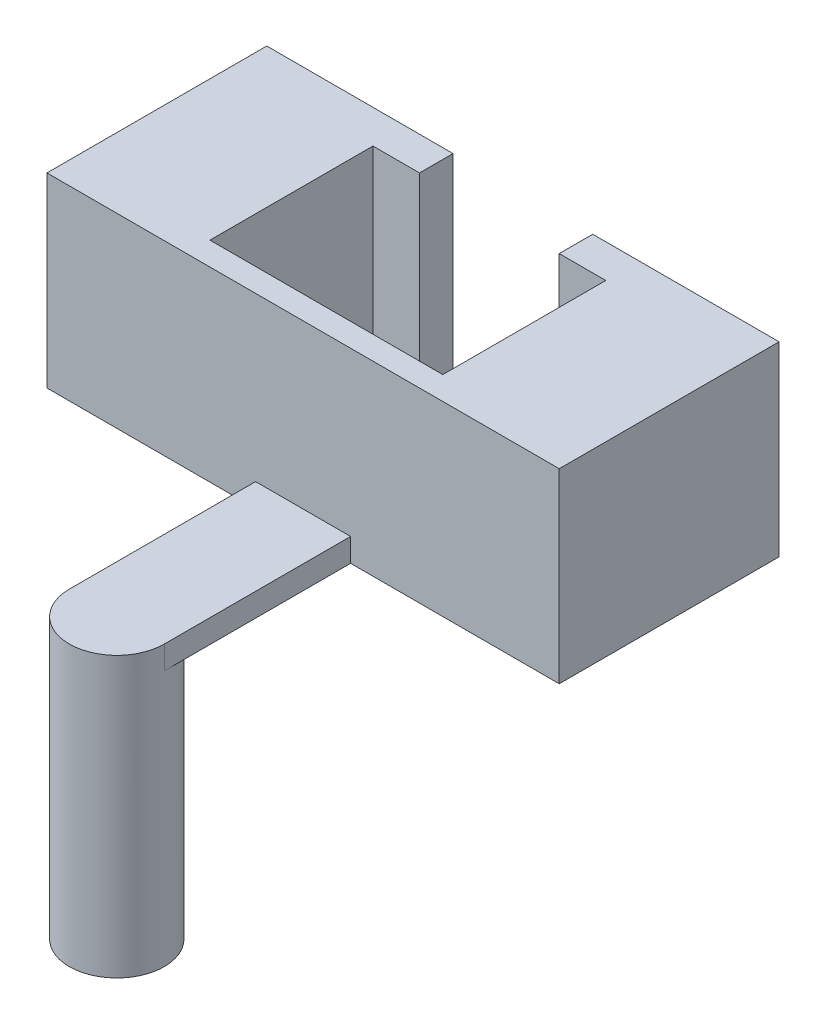
SolidWorks part; units mm, degrees
ref_plane "Front Plane" through (0, 0, 0) normal (0, 0, 1) x (1, 0, 0)
ref_plane "Top Plane" through (0, 0, 0) normal (0, 1, 0) x (1, 0, 0)
ref_plane "Right Plane" through (0, 0, 0) normal (1, 0, 0) x (0, 0, -1)
sketch "Sketch1" plane through (0, 0, 0) normal (0, 1, 0) x (1, 0, 0)
  circle A0 centre (-1.7341, 7.7072) radius 12.954
  dimension "D1" = 25.908
extrude "Boss-Extrude1" add sketch "Sketch1" along normal blind 76.2 contours A0
sketch "Sketch3" plane through (0, 76.2, 0) normal (0, 1, 0) x (1, 0, 0)
  line L1 (-14.6881, 7.7072) -> (11.2199, 7.7072)
  line L2 (-14.6881, 7.7072) -> (-14.6881, 58.5072)
  line L3 (-14.6881, 58.5072) -> (11.2199, 58.5072)
  line L4 (11.2199, 7.7072) -> (11.2199, 58.5072)
  circle A0 centre (-1.7341, 7.7072) radius 12.954 construction
  dimension "D1" = 50.8
  dimension "D2" = 25.908
extrude "Boss-Extrude3" add sketch "Sketch3" against normal blind 6.35
sketch "Sketch7" plane through (0, 0, -58.5072) normal (0, 0, -1) x (-1, 0, 0)
  line L0 (-11.2199, 69.85) -> (14.6881, 69.85) construction
  line L1 (-30.0159, 120.65) -> (33.4841, 120.65)
  line L2 (-30.0159, 120.65) -> (-30.0159, 69.85)
  line L3 (-30.0159, 69.85) -> (33.4841, 69.85)
  line L4 (33.4841, 120.65) -> (33.4841, 69.85)
  point P6 (1.7341, 69.85)
  point P7 (1.7341, 69.85)
  dimension "D1" = 50.8
  dimension "D2" = 63.5
extrude "Boss-Extrude4" add sketch "Sketch7" along normal blind 6.35
sketch "Sketch10" plane through (0, 69.85, 0) normal (0, -1, 0) x (1, 0, 0)
  line L1 (-33.4841, -58.5072) -> (-71.5841, -58.5072)
  line L2 (-33.4841, -58.5072) -> (-33.4841, -109.3072)
  line L3 (-33.4841, -109.3072) -> (-71.5841, -109.3072)
  line L4 (-71.5841, -58.5072) -> (-71.5841, -109.3072)
  line L5 (30.0159, -58.5072) -> (68.1159, -58.5072)
  line L6 (30.0159, -58.5072) -> (30.0159, -109.3072)
  line L7 (30.0159, -109.3072) -> (68.1159, -109.3072)
  line L8 (68.1159, -58.5072) -> (68.1159, -109.3072)
  point P10 (0, 0)
  point P11 (0, 0)
  point P12 (0, 0)
  point P13 (0, 0)
  dimension "D1" = 38.1
  dimension "D2" = 50.8
  dimension "D3" = 38.1
  dimension "D4" = 50.8
extrude "Boss-Extrude6" add sketch "Sketch10" against normal blind 50.8
sketch "Sketch11" plane through (0, 0, -109.3072) normal (0, 0, -1) x (-1, 0, 0)
  line L0 (-30.0159, 69.85) -> (33.4841, 69.85) construction
  line L1 (-68.1159, 120.65) -> (-17.3159, 120.65)
  line L2 (-68.1159, 120.65) -> (-68.1159, 69.85)
  line L3 (-68.1159, 69.85) -> (-17.3159, 69.85)
  line L4 (-17.3159, 120.65) -> (-17.3159, 69.85)
  line L6 (71.5841, 120.65) -> (20.7841, 120.65)
  line L7 (71.5841, 120.65) -> (71.5841, 69.85)
  line L8 (71.5841, 69.85) -> (20.7841, 69.85)
  line L9 (20.7841, 120.65) -> (20.7841, 69.85)
  dimension "D1" = 50.8
  dimension "D2" = 50.8
extrude "Boss-Extrude7" add sketch "Sketch11" along normal blind 9.144
equation "\"F\"= 600'lbf"
equation "\"P\"= \"F\" / 2 'lbf"
equation "\"P_DE\"= \"P\" / 2'lbf"
equation "\"SF\"= 4"
equation "\"Sy\"= 35000'psi"
equation "\"E\"= 10000000'psi"
equation "\"def\"= 0.005in "
equation "\"Sigma_allow\"= \"Sy\" / \"SF\"'psi"
equation "\"LA\"= 3in"
equation "\"DA\"= ( ( 64 * \"P\" * ( \"LA\" ) ^ 3 ) / ( 3 * PI * \"E\" * \"def\" ) ) ^ ( 1 / 4 ) "
equation "\"LB\"= \"DA\""
equation "\"hB\"= 2in"
equation "\"tB\"= 0.250in "
equation "\"LC\"= 2.5in"
equation "\"tC\" = 2in"
equation "\"hC\"= 0.2535in "
equation "\"LD\" = 1.498in"
equation "\"hD\" = 2in"
equation "\"tD\" = 0.25in"
equation "\"LE\"= 2in"
equation "\"tE\" = \"DA\""
equation "\"hE\"= ( ( 4 * \"P_DE\" * \"LE\" ^ 3 ) / ( \"E\" * \"tE\" * \"def\" ) ) ^ ( 1 / 3 )"
